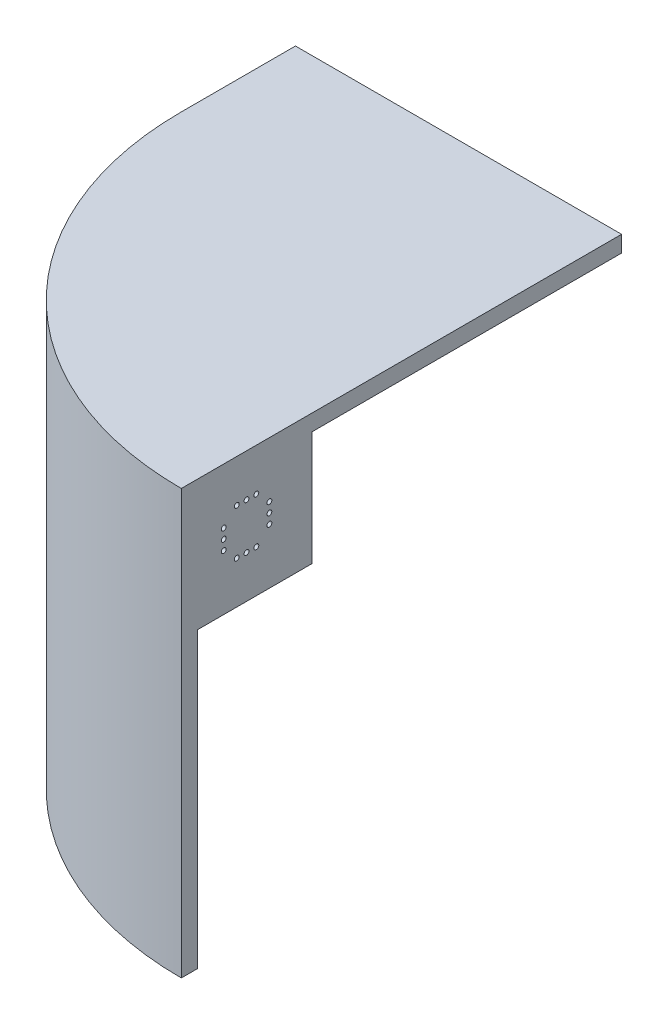
SolidWorks part; units mm, degrees
ref_plane "Front Plane" through (0, 0, 0) normal (0, 0, 1) x (1, 0, 0)
ref_plane "Top Plane" through (0, 0, 0) normal (0, 1, 0) x (1, 0, 0)
ref_plane "Right Plane" through (0, 0, 0) normal (1, 0, 0) x (0, 0, -1)
sketch "Sketch2" plane through (0, 0, 0) normal (0, 1, 0) x (1, 0, 0)
  line L0 (0, -100) -> (0, 35)
  line L1 (0, 35) -> (-100, 35)
  line L2 (-100, 35) -> (-100, 0)
  arc A0 (-100, 0) -> (0, -100) centre (0, 0) ccw
  dimension "D1" = 200
  dimension "D2" = 135
  dimension "D3" = 100
  dimension "D4" = 35
extrude "Boss-Extrude1" add sketch "Sketch2" along normal blind 130
sketch "Sketch3" plane through (0, 0, 0) normal (0, -1, 0) x (1, 0, 0)
  line L0 (0, 95) -> (0, -35)
  line L1 (0, -35) -> (-100, -35)
  line L2 (0, -35) -> (-100, -35) construction
  line L3 (-100, -35) -> (-95, 0)
  arc A0 (0, 95) -> (-95, 0) centre (0, 0) ccw
  point P6 (0, 0)
  dimension "D1" = 190
  dimension "D2" = 35
  dimension "D3" = 100
extrude "Cut-Extrude1" cut sketch "Sketch3" against normal blind 125
sketch "Sketch7" plane through (0, 0, 0) normal (1, 0, 0) x (0, 0, -1)
  line L2 (-95, 125) -> (-60, 125)
  line L3 (-95, 125) -> (-95, 90)
  line L4 (-95, 90) -> (-60, 90)
  line L5 (-60, 125) -> (-60, 90)
  dimension "D1" = 35
  dimension "D2" = 35
extrude "Boss-Extrude3" add sketch "Sketch7" against normal blind 5
sketch "Sketch8" plane through (0, 0, 0) normal (1, 0, 0) x (0, 0, -1)
  line L3 (-100, 130) -> (-100, 0) construction
  line L4 (-100, 130) -> (35, 130) construction
  circle A1 centre (-87, 110) radius 0.75
  circle A2 centre (-87, 107) radius 0.75
  circle A3 centre (-87, 113) radius 0.75
  circle A4 centre (-77, 117) radius 0.75
  circle A5 centre (-80, 117) radius 0.75
  circle A6 centre (-83, 117) radius 0.75
  circle A7 centre (-73, 107) radius 0.75
  circle A8 centre (-73, 110) radius 0.75
  circle A9 centre (-73, 113) radius 0.75
  circle A10 centre (-83, 103) radius 0.75
  circle A11 centre (-80, 103) radius 0.75
  circle A12 centre (-77, 103) radius 0.75
  point P10 (-80, 110)
  dimension "D1" = 13
  dimension "D2" = 20
  dimension "D3" = 1.5
  dimension "D4" = 1.5
  dimension "D5" = 1.5
  dimension "D6" = 3
  dimension "D7" = 3
  dimension "D8" = 4
extrude "Cut-Extrude2" cut sketch "Sketch8" against normal up to surface (5 mm away) up to face at (-5, 107.5, 77.4342)
